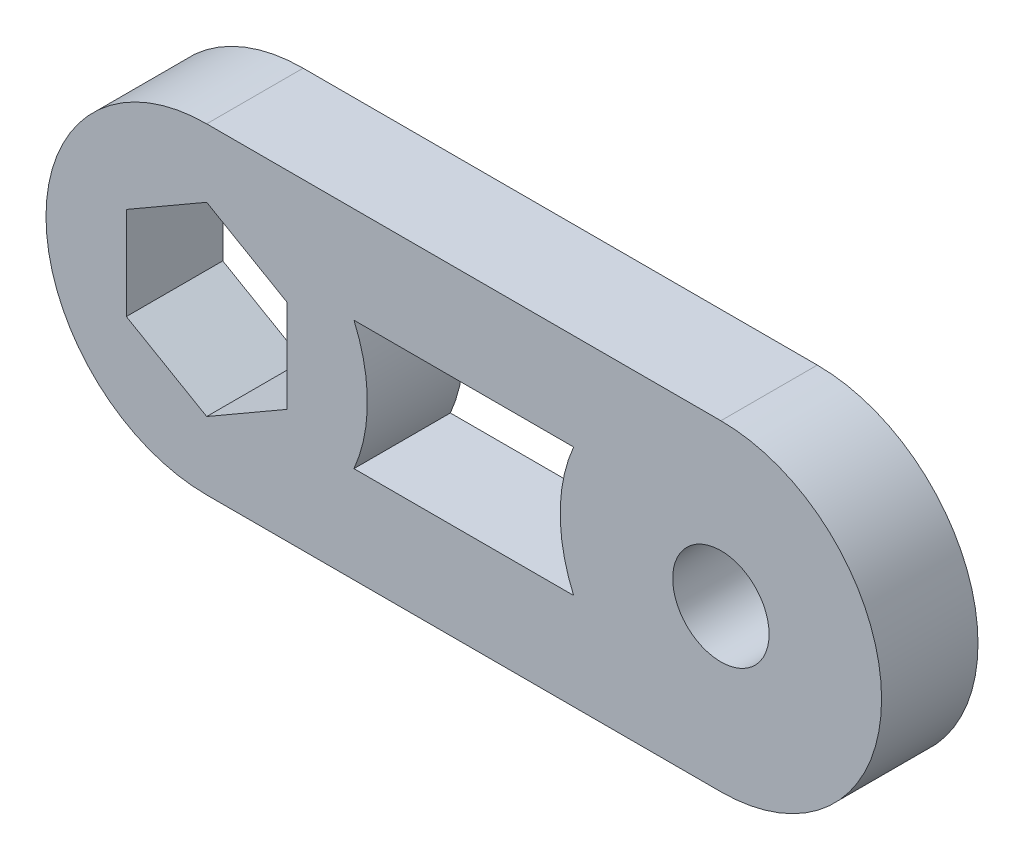
SolidWorks part; units mm, degrees
material "Plain Carbon Steel"
ref_plane "Front Plane" through (0, 0, 0) normal (0, 0, 1) x (1, 0, 0)
ref_plane "Top Plane" through (0, 0, 0) normal (0, 1, 0) x (1, 0, 0)
ref_plane "Right Plane" through (0, 0, 0) normal (1, 0, 0) x (0, 0, -1)
sketch "Sketch1" plane through (0, 0, 0) normal (0, 0, 1) x (1, 0, 0)
  line L0 (0, 0) -> (16, 0)
  line L1 (0, -5) -> (16, -5)
  line L2 (0, 5) -> (16, 5)
  circle A0 centre (16, 0) radius 1.5
  circle A1 centre (0, 0) radius 1.5
  arc A2 (0, -5) -> (0, 5) centre (0, 0) cw
  arc A3 (16, -5) -> (16, 5) centre (16, 0) ccw
  dimension "D2" = 3
  dimension "D1" = 3
extrude "Extrude1" add sketch "Sketch1" along normal blind 3
sketch "Sketch2" plane through (0, 0, 3) normal (0, 0, 1) x (1, 0, 0)
  line L1 (0, 2.8868) -> (-2.5, 1.4434)
  line L2 (-2.5, 1.4434) -> (-2.5, -1.4434)
  line L3 (-2.5, -1.4434) -> (0, -2.8868)
  line L4 (0, -2) -> (16, -2)
  line L5 (16, 2) -> (0, 2)
  line L6 (4.5826, -2) -> (11.4174, -2)
  line L7 (11.4174, 2) -> (4.5826, 2)
  line L8 (0, -2.8868) -> (2.5, -1.4434)
  line L9 (2.5, -1.4434) -> (2.5, 1.4434)
  line L10 (2.5, 1.4434) -> (0, 2.8868)
  circle A0 centre (16, 0) radius 1.5
  circle A1 centre (0, 0) radius 2.5 construction
  arc A2 (4.5826, -2) -> (4.5826, 2) centre (0, 0) ccw
  arc A3 (11.4174, 2) -> (11.4174, -2) centre (16, 0) ccw
  arc A4 (16, -2) -> (16, 2) centre (16, 0) ccw
  arc A5 (0, 2) -> (0, -2) centre (0, 0) ccw
  dimension "D2" = 3
  dimension "D3" = 5
  dimension "D1" = 3
extrude "Cut-Extrude1" cut sketch "Sketch2" against normal blind 10
move or copy body "Body-Move/Copy1" [suppressed] bodies to move or copy 103
move or copy body "Body-Move/Copy2" [suppressed] bodies to move or copy 103
move or copy body "Body-Move/Copy3" [suppressed] bodies to move or copy 103
